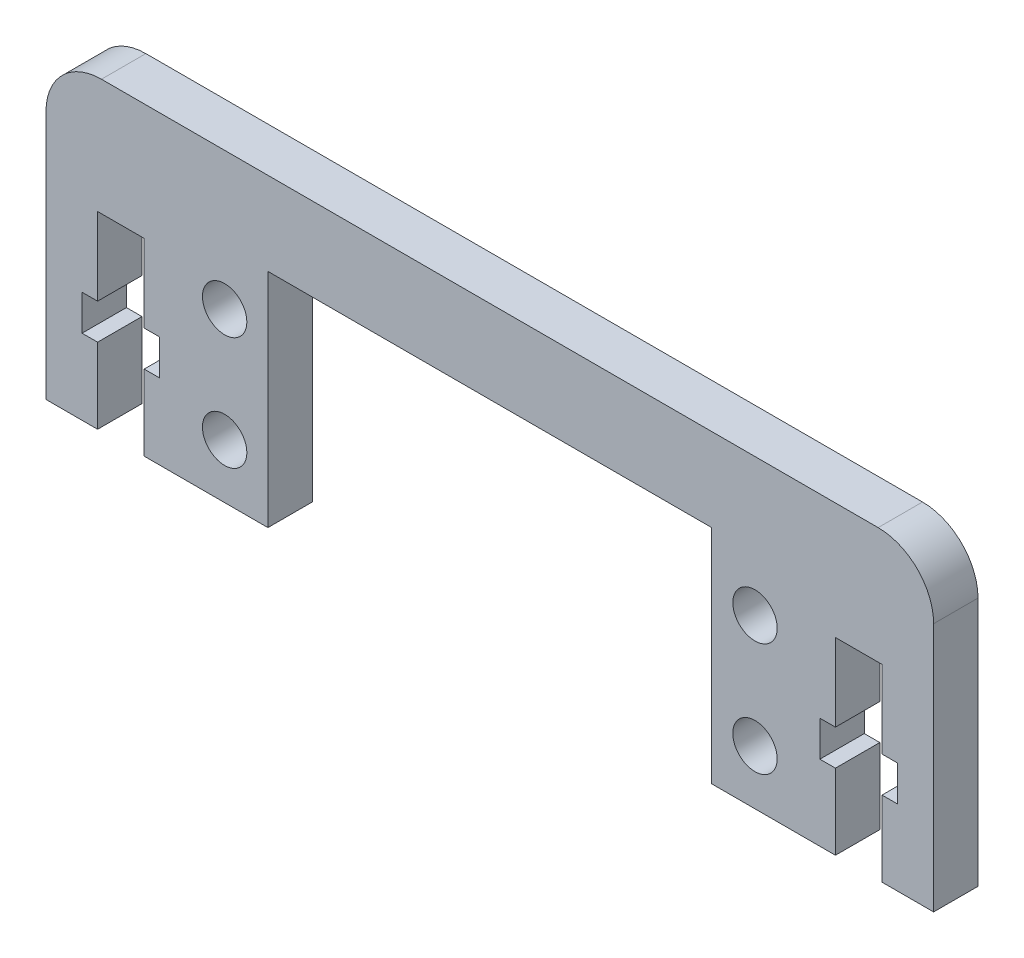
SolidWorks part; units mm, degrees
ref_plane "Plan de face" through (0, 0, 0) normal (0, 0, 1) x (1, 0, 0)
ref_plane "Plan de dessus" through (0, 0, 0) normal (0, 1, 0) x (1, 0, 0)
ref_plane "Plan de droite" through (0, 0, 0) normal (1, 0, 0) x (0, 0, -1)
sketch "Esquisse1" plane through (0, 0, 0) normal (0, 0, 1) x (1, 0, 0)
  line L1 (-40, -13.75) -> (40, -13.75)
  line L2 (-40, -13.75) -> (-40, 13.75)
  line L3 (-40, 13.75) -> (40, 13.75)
  line L4 (40, -13.75) -> (40, 13.75)
  line L5 (-40, -13.75) -> (40, 13.75) construction
  line L6 (-40, 13.75) -> (40, -13.75) construction
  point P0 (0, 0)
  dimension "D1" = 80
  dimension "D2" = 27.5
extrude "Boss.-Extru.1" add sketch "Esquisse1" along normal blind 4
sketch "Esquisse2" plane through (0, 0, 0) normal (0, 0, -1) x (-1, 0, 0)
  line L0 (40, -13.75) -> (-40, -13.75) construction
  line L1 (20, 6.25) -> (-20, 6.25)
  line L2 (20, 6.25) -> (20, -13.75)
  line L3 (20, -13.75) -> (-20, -13.75)
  line L4 (-20, 6.25) -> (-20, -13.75)
  line L8 (40, 13.75) -> (40, -13.75) construction
  line L9 (20, -3.75) -> (-20, -3.75) construction
  line L10 (0, -3.75) -> (0, 6.25) construction
  circle A2 centre (-23.9, 1.35) radius 2
  circle A4 centre (-23.9, -8.85) radius 2
  circle A5 centre (23.9, -8.85) radius 2
  circle A6 centre (23.9, 1.35) radius 2
  point P8 (40, 0)
  dimension "D4" = 4
  dimension "D1" = 20
  dimension "D2" = 40
  dimension "D3" = 20
  dimension "D6" = 3.9
  dimension "D7" = 5.1
extrude "Enlèv. mat.-Extru.1" cut sketch "Esquisse2" against normal through all
sketch "Esquisse3" plane through (0, 0, 0) normal (0, 0, -1) x (-1, 0, 0)
  line L0 (0, 0) -> (0, 13.75) construction
  line L1 (-40, 13.75) -> (40, 13.75) construction
  line L2 (40, -13.75) -> (20, -13.75) construction
  line L3 (26.5, -3.75) -> (40, -3.75) construction
  line L4 (40, 13.75) -> (40, -13.75) construction
  line L5 (33.25, -13.75) -> (33.25, 13.75) construction
  line L6 (40, -13.75) -> (20, -13.75) construction
  line L7 (31.15, -13.75) -> (35.35, -13.75)
  line L8 (35.35, -13.75) -> (35.35, -6.95)
  line L9 (35.35, -6.95) -> (36.75, -6.95)
  line L10 (36.75, -6.95) -> (36.75, -3.75)
  line L11 (36.75, -3.75) -> (35.35, -3.75)
  line L12 (35.35, -3.75) -> (35.35, 3.25)
  line L13 (35.35, 3.25) -> (31.15, 3.25)
  line L14 (31.15, -3.75) -> (31.15, 3.25)
  line L15 (29.75, -3.75) -> (31.15, -3.75)
  line L16 (29.75, -6.95) -> (29.75, -3.75)
  line L17 (31.15, -6.95) -> (29.75, -6.95)
  line L18 (31.15, -13.75) -> (31.15, -6.95)
  line L19 (-31.15, -13.75) -> (-31.15, -6.95)
  line L20 (-31.15, -6.95) -> (-29.75, -6.95)
  line L21 (-29.75, -6.95) -> (-29.75, -3.75)
  line L22 (-29.75, -3.75) -> (-31.15, -3.75)
  line L23 (-31.15, -3.75) -> (-31.15, 3.25)
  line L24 (-35.35, 3.25) -> (-31.15, 3.25)
  line L25 (-35.35, -3.75) -> (-35.35, 3.25)
  line L26 (-36.75, -3.75) -> (-35.35, -3.75)
  line L27 (-36.75, -6.95) -> (-36.75, -3.75)
  line L28 (-35.35, -6.95) -> (-36.75, -6.95)
  line L29 (-35.35, -13.75) -> (-35.35, -6.95)
  line L30 (-31.15, -13.75) -> (-35.35, -13.75)
  line L31 (40, 13.75) -> (40, -13.75) construction
  point P25 (33.25, 3.25)
  point P30 (33.25, -3.75)
  point P44 (-33.25, 3.25)
  dimension "D1" = 7
  dimension "D2" = 4.2
  dimension "D3" = 10
  dimension "D4" = 17
  dimension "D5" = 3.2
  dimension "D6" = 10
  dimension "D7" = 6.75
extrude "Enlèv. mat.-Extru.2" cut sketch "Esquisse3" against normal through all
fillet "Congé1" radius 5 2 edges at (40, 13.75, 2) (-40, 13.75, 2)
